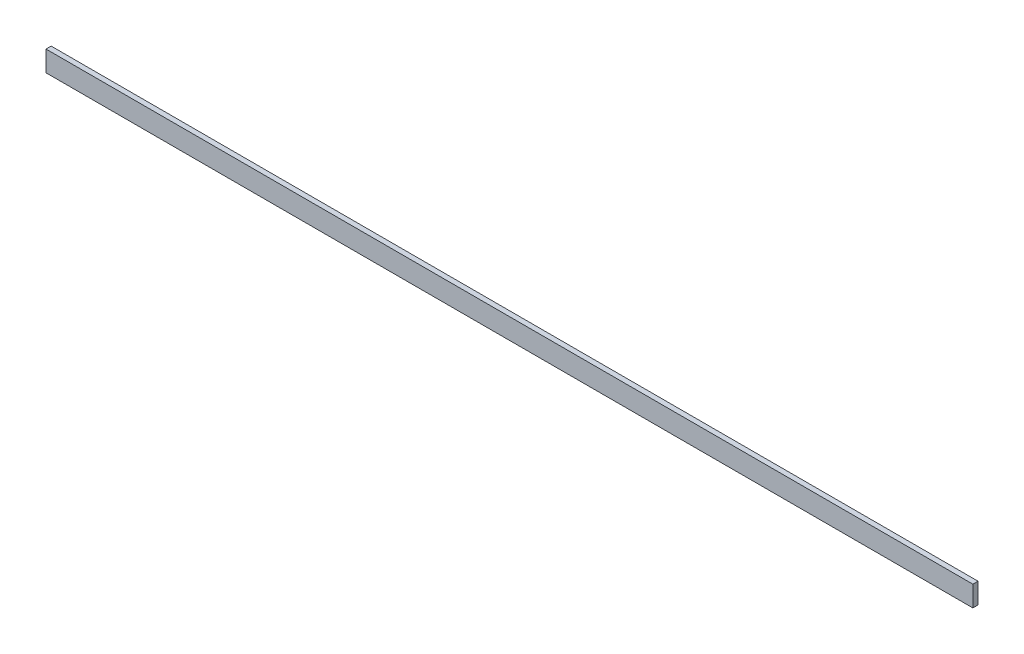
SolidWorks part; units mm, degrees
ref_plane "Front Plane" through (0, 0, 0) normal (0, 0, 1) x (1, 0, 0)
ref_plane "Top Plane" through (0, 0, 0) normal (0, 1, 0) x (1, 0, 0)
ref_plane "Right Plane" through (0, 0, 0) normal (1, 0, 0) x (0, 0, -1)
sketch "Sketch1" plane through (0, 0, 0) normal (0, 0, 1) x (1, 0, 0)
  line L1 (0, 0) -> (457.2, 0)
  line L2 (0, 0) -> (0, 10.16)
  line L3 (0, 10.16) -> (457.2, 10.16)
  line L4 (457.2, 0) -> (457.2, 10.16)
  dimension "D1" = 10.16
  dimension "D2" = 457.2
extrude "Boss-Extrude1" add sketch "Sketch1" along normal blind 2.54
sketch "Sketch2" plane through (0, 0, 0) normal (0, 0, -1) x (-1, 0, 0)
  line L0 (-457.2, 0) -> (-457.2, 10.16) construction
  line L1 (0, 0) -> (-457.2, 0) construction
  circle A0 centre (-447.675, 4.7625) radius 3.175
  dimension "D1" = 6.35
  dimension "D2" = 9.525
  dimension "D3" = 4.7625
extrude "Boss-Extrude2" add sketch "Sketch2" along normal blind 1.27 contours A0
pattern_linear "LPattern1" count 23 spacing 19.05 along (-1, 0, 0) of "Boss-Extrude2"
